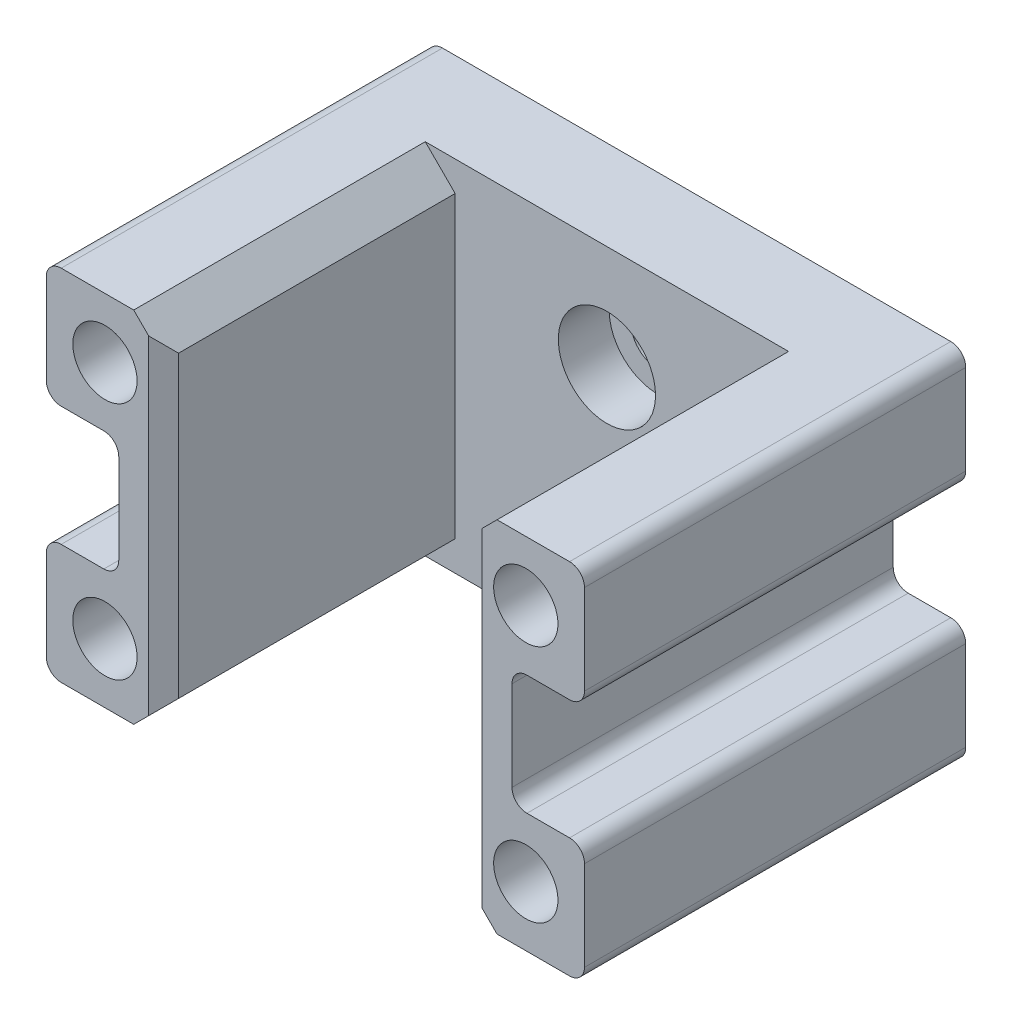
SolidWorks part; units mm, degrees
ref_plane "Płaszczyzna przednia" through (0, 0, 0) normal (0, 0, 1) x (1, 0, 0)
ref_plane "Płaszczyzna górna" through (0, 0, 0) normal (0, 1, 0) x (1, 0, 0)
ref_plane "Płaszczyzna prawa" through (0, 0, 0) normal (1, 0, 0) x (0, 0, -1)
sketch "Sketch1" plane through (0, 0, 0) normal (0, 0, 1) x (1, 0, 0)
  line L1 (0, 0) -> (36, 0)
  line L2 (0, 0) -> (0, 24)
  line L3 (0, 24) -> (36, 24)
  line L4 (36, 0) -> (36, 24)
  dimension "D1" = 24
  dimension "D2" = 36
extrude "Boss-Extrude1" add sketch "Sketch1" along normal blind 6
hole_wizard "CBORE for M3 Hex Socket Head Cap Screw1" positions "Sketch2" profile "Sketch3" counterbore size "M3" standard "DIN"
sketch "Sketch2" plane through (0, 0, 6) normal (0, 0, 1) x (1, 0, 0)
  line L0 (18, 0) -> (18, 7) construction
  line L1 (0, 0) -> (36, 0) construction
  line L2 (18, 7) -> (18, 17) construction
  line L4 (18, 17) -> (18, 24) construction
  line L5 (36, 24) -> (0, 24) construction
  point P0 (18, 17)
  point P2 (18, 7)
  dimension "D1" = 10
sketch "Sketch3" plane through (18, 17, 6) normal (1, 0, 0) x (0, -1, 0)
  line L0 (0, 0) -> (0, 13.0815)
  line L1 (0, 13.0815) -> (1.8, 12)
  line L2 (1.8, 12) -> (1.8, 3.4)
  line L3 (1.8, 3.4) -> (3.25, 3.4)
  line L4 (3.25, 3.4) -> (3.25, 0)
  line L5 (3.25, 0) -> (0, 0)
  line L10 (0, 13.0815) -> (-1.8, 12) construction
  line L11 (0, -6.35) -> (0, 107.95) construction
  dimension "Hole Dia." = 3.6
  dimension "Hole Depth" = 12
  dimension "C'Bore Dia." = 6.5
  dimension "C'Bore Depth" = 3.4
  dimension "Drill Angle" = 118
sketch "Sketch4" plane through (0, 0, 6) normal (0, 0, 1) x (1, 0, 0)
  line L0 (0, 0) -> (36, 0) construction
  line L1 (0, 24) -> (7.85, 24)
  line L2 (0, 24) -> (0, 16)
  line L3 (0, 0) -> (7.85, 0)
  line L10 (0, 8) -> (0, 0)
  line L11 (0, 24) -> (7.85, 24)
  line L12 (0, 24) -> (0, 16)
  line L13 (0, 16) -> (4.85, 16)
  line L18 (4.85, 16) -> (4.85, 8)
  line L19 (7.85, 0) -> (0, 0)
  line L21 (4.85, 8) -> (0, 8)
  line L22 (0, 0) -> (0, 8)
  line L23 (7.85, 0) -> (7.85, 24)
  line L24 (18, 17) -> (18, 7) construction
  line L25 (36, 0) -> (28.15, 0)
  line L26 (36, 8) -> (36, 0)
  line L27 (31.15, 8) -> (36, 8)
  line L28 (31.15, 16) -> (31.15, 8)
  line L29 (36, 16) -> (31.15, 16)
  line L30 (36, 24) -> (36, 16)
  line L31 (36, 24) -> (28.15, 24)
  line L32 (28.15, 0) -> (28.15, 24)
  line M8 (0, 24) -> (0, 0)
  line M9 (0, 0) -> (36, 0)
  line M10 (36, 0) -> (36, 24)
  line M11 (36, 24) -> (0, 24)
  dimension "D1" = 7.85
  dimension "D2" = 8
extrude "Boss-Extrude2" add sketch "Sketch4" along normal blind 19.5 contours L23 L13 L18 L21 M9 M11 M8 | L32 L27 L28 L29 M9 M10 M11
sketch "Sketch5" plane through (0, 0, 6) normal (0, 0, 1) x (1, 0, 0)
  line L0 (31.15, 16) -> (31.15, 8) construction
  line L1 (31.15, 8) -> (36, 8) construction
  line L2 (36, 8) -> (36, 16) construction
  line L3 (36, 16) -> (31.15, 16) construction
  line L4 (0, 8) -> (4.85, 8) construction
  line L5 (4.85, 8) -> (4.85, 16) construction
  line L6 (4.85, 16) -> (0, 16) construction
  line L7 (0, 16) -> (0, 8) construction
  line L8 (31.15, 16) -> (31.15, 8)
  line L9 (31.15, 8) -> (36, 8)
  line L10 (36, 8) -> (36, 16)
  line L11 (36, 16) -> (31.15, 16)
  line L12 (0, 8) -> (4.85, 8)
  line L13 (4.85, 8) -> (4.85, 16)
  line L14 (4.85, 16) -> (0, 16)
  line L15 (0, 16) -> (0, 8)
extrude "Cut-Extrude1" cut sketch "Sketch5" against normal through all
hole_wizard "Ø4.3 (4.3) Diameter Hole1" positions "Sketch8" profile "Sketch9" hole size "Ø4.3" standard "DIN"
sketch "Sketch8" plane through (0, 0, 25.5) normal (0, 0, 1) x (1, 0, 0)
  line L0 (0, 4) -> (3.925, 4) construction
  line L1 (0, 8) -> (0, 0) construction
  line L3 (0, 20) -> (3.925, 20) construction
  line L4 (0, 24) -> (0, 16) construction
  line L6 (3.925, 24) -> (3.925, 20) construction
  line L7 (7.85, 24) -> (0, 24) construction
  line L9 (3.925, 4) -> (3.925, 20) construction
  line L11 (18, 17) -> (18, 7) construction
  point P0 (3.925, 20)
  point P2 (3.925, 4)
  point P34 (32.075, 4)
  point P35 (32.075, 20)
sketch "Sketch9" plane through (3.925, 20, 25.5) normal (1, 0, 0) x (0, -1, 0)
  line L0 (0, 0) -> (0, 17.2919)
  line L1 (0, 17.2919) -> (2.15, 16)
  line L2 (2.15, 16) -> (2.15, 0)
  line L5 (2.15, 0) -> (0, 0)
  line L10 (0, 17.2919) -> (-2.15, 16) construction
  line L11 (0, -6.35) -> (0, 107.95) construction
  dimension "Hole Dia." = 4.3
  dimension "Hole Depth" = 16
  dimension "Drill Angle" = 118
fillet "Fillet1" radius 1 12 edges at (0, 16, 12.75) (4.85, 16, 12.75) (4.85, 8, 12.75) (0, 8, 12.75) (36, 8, 12.75) (31.15, 8, 12.75) (31.15, 16, 12.75) (36, 16, 12.75) (0, 24, 12.75) (36, 24, 12.75) (36, 0, 12.75) (0, 0, 12.75)
chamfer "Chamfer1" distance 2 angle 45 4 edges at (28.15, 0, 15.75) (28.15, 24, 15.75) (7.85, 24, 15.75) (7.85, 0, 15.75)
chamfer "Chamfer2" distance 1 angle 45 2 edges at (28.15, 12, 25.5) (7.85, 12, 25.5)
